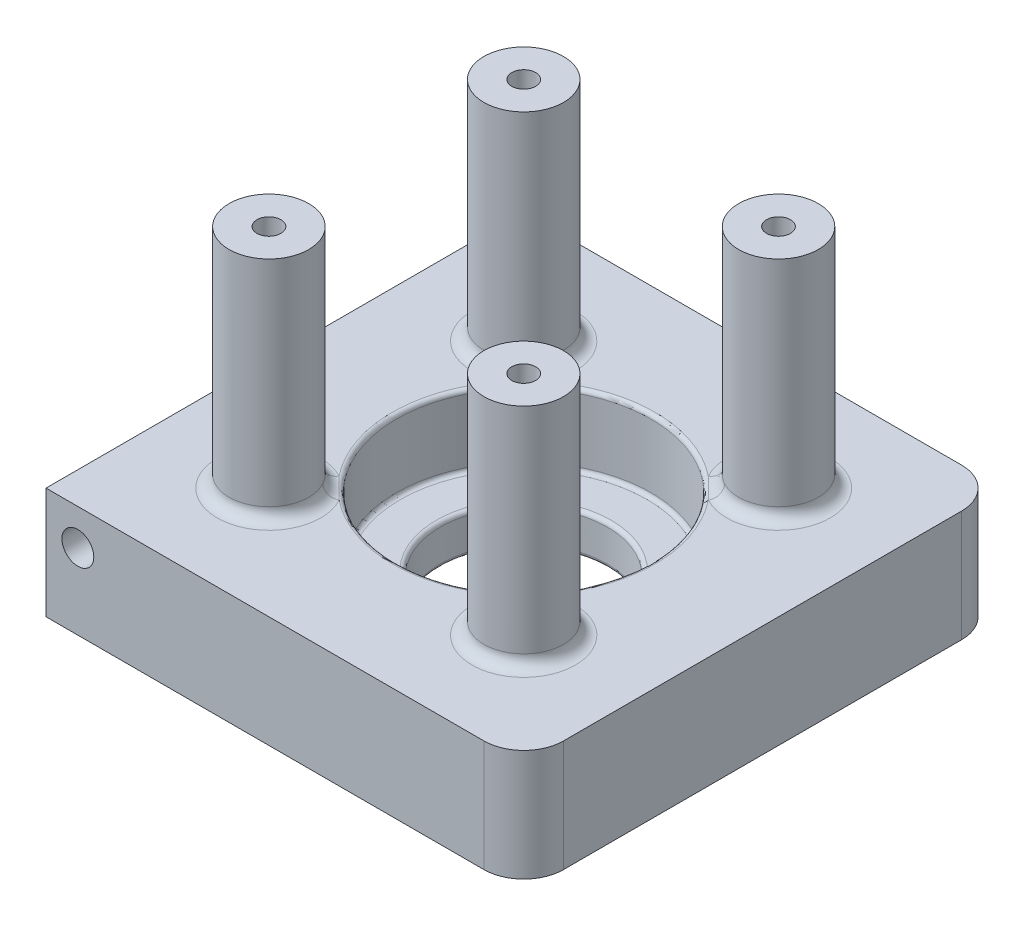
SolidWorks part; units mm, degrees
material "ABS"
ref_plane "Front Plane" through (0, 0, 0) normal (0, 0, 1) x (1, 0, 0)
ref_plane "Top Plane" through (0, 0, 0) normal (0, 1, 0) x (1, 0, 0)
ref_plane "Right Plane" through (0, 0, 0) normal (1, 0, 0) x (0, 0, -1)
other "Configuration Table"
sketch "Sketch1" plane through (0, 0, 0) normal (0, 1, 0) x (1, 0, 0)
  line L1 (30, -30) -> (-30, -30)
  line L2 (30, -30) -> (30, 30)
  line L3 (30, 30) -> (-30, 30)
  line L4 (-30, -30) -> (-30, 30)
  line L5 (30, -30) -> (-30, 30) construction
  line L6 (30, 30) -> (-30, -30) construction
  point P0 (0, 0)
  dimension "D1" = 60
extrude "Boss-Extrude1" add sketch "Sketch1" along normal blind 20
sketch "Sketch2" plane through (0, 20, 0) normal (0, 1, 0) x (1, 0, 0)
  circle A0 centre (0, 0) radius 7.5
  dimension "D1" = 15
extrude "Cut-Extrude1" cut sketch "Sketch2" against normal blind 20
sketch "Sketch3" plane through (0, 20, 0) normal (0, 1, 0) x (1, 0, 0)
  circle A0 centre (0, 0) radius 16
  dimension "D1" = 32
extrude "Cut-Extrude2" cut sketch "Sketch3" against normal blind 9
fillet "Fillet1" radius 0.5 4 edges at (0, 0, 7.5) (0, 11, 7.5) (0, 20, 16) (0, 11, 16)
sketch "Sketch4" plane through (0, 0, 0) normal (0, -1, 0) x (1, 0, 0)
  line L1 (25, -25) -> (-25, -25)
  line L2 (25, -25) -> (25, 25)
  line L3 (25, 25) -> (-25, 25)
  line L4 (-25, -25) -> (-25, 25)
  line L5 (25, -25) -> (-25, 25) construction
  line L6 (25, 25) -> (-25, -25) construction
  point P0 (0, 0)
  dimension "D1" = 50
extrude "Cut-Extrude3" cut sketch "Sketch4" against normal blind 6
sketch "Sketch5" plane through (0, 6, 0) normal (0, -1, 0) x (1, 0, 0)
  line L1 (16, -16) -> (-16, -16) construction
  line L2 (16, -16) -> (16, 16) construction
  line L3 (16, 16) -> (-16, 16) construction
  line L4 (-16, -16) -> (-16, 16) construction
  line L5 (16, -16) -> (-16, 16) construction
  line L6 (16, 16) -> (-16, -16) construction
  circle A0 centre (-16, 16) radius 1.5
  circle A1 centre (-16, -16) radius 1.5
  circle A2 centre (16, -16) radius 1.5
  circle A3 centre (16, 16) radius 1.5
  point P0 (0, 0)
  dimension "D2" = 3
  dimension "D3" = 3
  dimension "D4" = 3
  dimension "D5" = 3
  dimension "D1" = 32
sketch "Sketch6" plane through (0, 20, 0) normal (0, 1, 0) x (1, 0, 0)
  circle A0 centre (-16, 16) radius 5
  circle A1 centre (16, 16) radius 5
  circle A2 centre (-16, -16) radius 5
  circle A3 centre (16, -16) radius 5
  dimension "D1" = 10
  dimension "D2" = 10
  dimension "D3" = 10
  dimension "D4" = 10
extrude "Boss-Extrude2" add sketch "Sketch6" along normal blind 28.45
extrude "Cut-Extrude5" cut sketch "Sketch5" against normal blind 54.45
sketch "Sketch7" plane through (0, 6, 0) normal (0, -1, 0) x (1, 0, 0)
  circle A0 centre (-16, 16) radius 3
  circle A1 centre (-16, -16) radius 3
  circle A2 centre (16, -16) radius 3
  circle A3 centre (16, 16) radius 3
  dimension "D1" = 6
  dimension "D2" = 6
  dimension "D3" = 6
  dimension "D4" = 6
extrude "Cut-Extrude6" cut sketch "Sketch7" against normal blind 3
fillet "Fillet2" radius 1.5 4 edges at (-16, 20, 21) (16, 20, 21) (16, 20, -11) (-16, 20, -11)
sketch "Sketch8" plane through (0, 6, 0) normal (0, -1, 0) x (1, 0, 0)
  circle A0 centre (0, 0) radius 10.5
  dimension "D1" = 21
extrude "Cut-Extrude7" cut sketch "Sketch8" against normal blind 9
fillet "Fillet3" radius 0.5 2 edges at (0, 6, -10.5) (0, 11, 10.5)
sketch "Sketch9" plane through (0, 0, 0) normal (0, -1, 0) x (1, 0, 0)
  line L0 (-30, -30) -> (-30, 30)
  line L1 (-30, 30) -> (30, 30)
  line L2 (30, 30) -> (30, -30)
  line L3 (30, -30) -> (-30, -30)
  line L4 (-25, 25) -> (25, 25)
  line L5 (25, 25) -> (25, -25)
  line L6 (25, -25) -> (-25, -25)
  line L7 (-25, -25) -> (-25, 25)
extrude "Cut-Extrude8" cut sketch "Sketch9" against normal blind 6
sketch "Sketch10" plane through (0, 6, 0) normal (0, -1, 0) x (1, 0, 0)
  line L1 (25, -25) -> (-25, -25) construction
  line L2 (25, -25) -> (25, 25) construction
  line L3 (25, 25) -> (-25, 25) construction
  line L4 (-25, -25) -> (-25, 25) construction
  line L5 (25, -25) -> (-25, 25) construction
  line L6 (25, 25) -> (-25, -25) construction
  circle A0 centre (-25, 25) radius 2
  circle A1 centre (-25, -25) radius 2
  circle A2 centre (25, -25) radius 2
  circle A3 centre (25, 25) radius 2
  point P0 (0, 0)
  dimension "D2" = 4
  dimension "D3" = 4
  dimension "D4" = 4
  dimension "D5" = 4
  dimension "D1" = 50
extrude "Cut-Extrude9" cut sketch "Sketch10" against normal blind 6
fillet "Fillet4" radius 5 2 edges at (30, 13, -30) (30, 13, 30)
sketch "Sketch11" plane through (0, 0, 30) normal (0, 0, 1) x (1, 0, 0)
  circle A0 centre (-26, 15.4965) radius 2
  dimension "D1" = 4
extrude "Cut-Extrude10" cut sketch "Sketch11" against normal blind 14
sketch "Sketch12" plane through (0, 0, -30) normal (0, 0, -1) x (-1, 0, 0)
  circle A0 centre (26, 15.4965) radius 2
  dimension "D1" = 4
extrude "Cut-Extrude11" cut sketch "Sketch12" against normal blind 14
